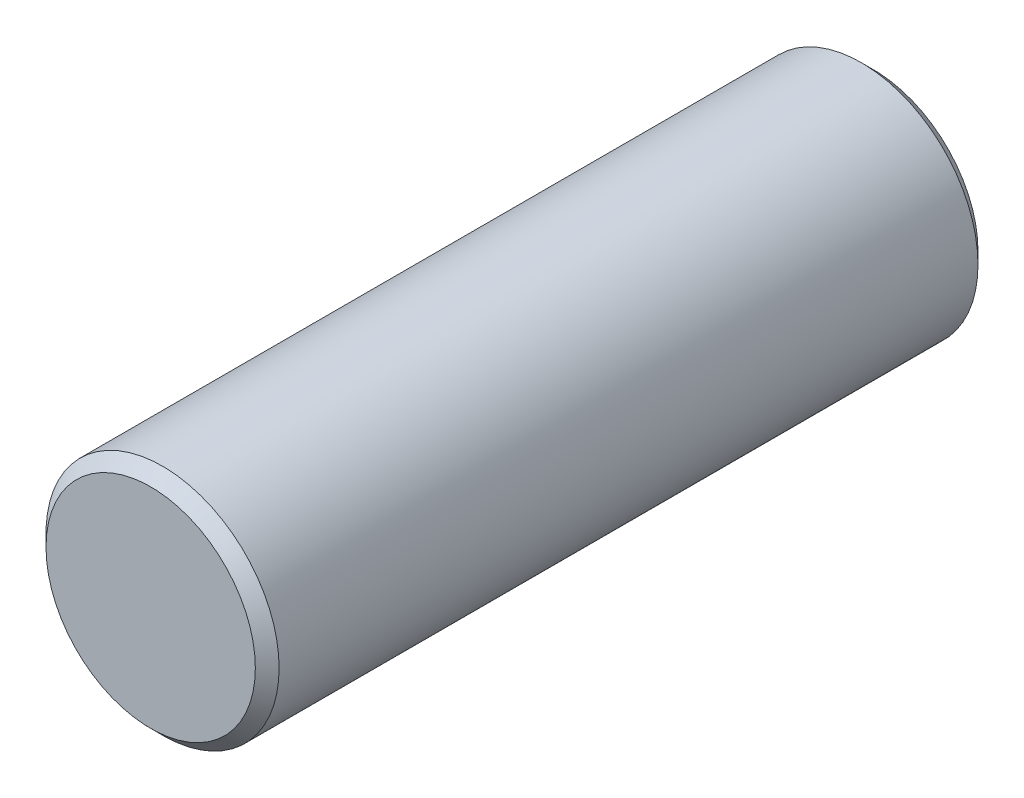
SolidWorks part; units mm, degrees
ref_plane "Front Plane" through (0, 0, 0) normal (0, 0, 1) x (1, 0, 0)
ref_plane "Top Plane" through (0, 0, 0) normal (0, 1, 0) x (1, 0, 0)
ref_plane "Right Plane" through (0, 0, 0) normal (1, 0, 0) x (0, 0, -1)
sketch "Sketch1" plane through (0, 0, 0) normal (0, 0, 1) x (1, 0, 0)
  circle A0 centre (0, 0) radius 5
  dimension "D1" = 10
extrude "Boss-Extrude1" add sketch "Sketch1" along normal mid plane 31
chamfer "Chamfer1" distance 0.51 angle 45 2 edges at (5, 0, -15.5) (5, 0, 15.5)
